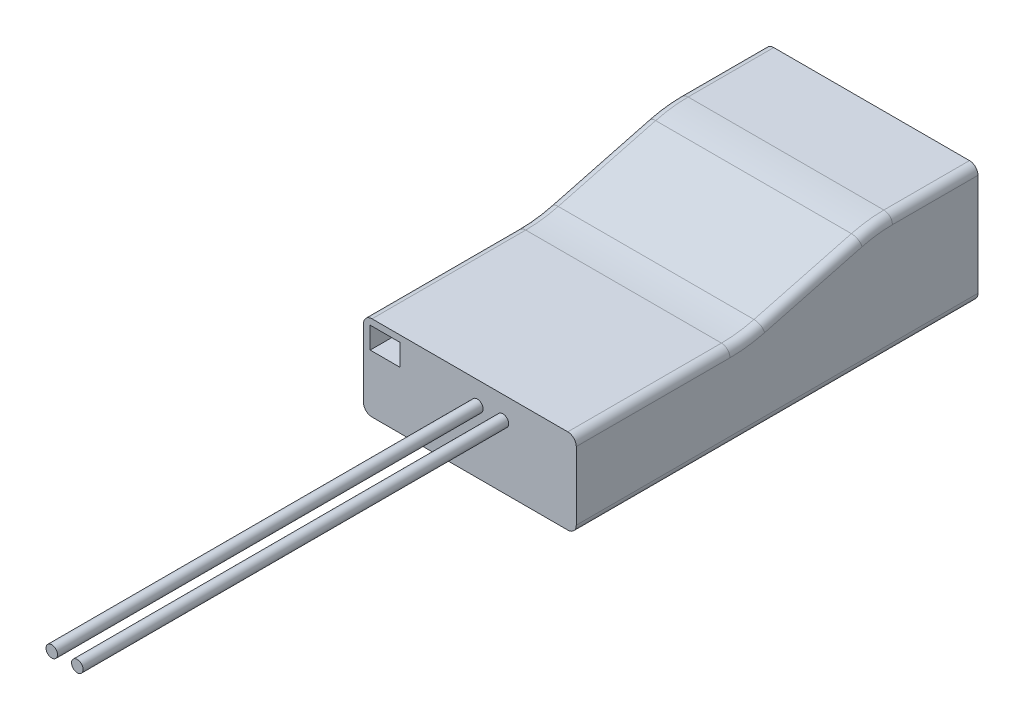
SolidWorks part; units mm, degrees
ref_plane "前基準面" through (0, 0, 0) normal (0, 0, 1) x (1, 0, 0)
ref_plane "上基準面" through (0, 0, 0) normal (0, 1, 0) x (1, 0, 0)
ref_plane "右基準面" through (0, 0, 0) normal (1, 0, 0) x (0, 0, -1)
sketch "草圖1" plane through (0, 0, 0) normal (0, 1, 0) x (1, 0, 0)
  line L1 (-12.5, 23.6) -> (12.5, 23.6)
  line L2 (-12.5, 23.6) -> (-12.5, -23.6)
  line L3 (-12.5, -23.6) -> (12.5, -23.6)
  line L4 (12.5, 23.6) -> (12.5, -23.6)
  line L5 (-12.5, 23.6) -> (12.5, -23.6) construction
  line L6 (-12.5, -23.6) -> (12.5, 23.6) construction
  point P0 (0, 0)
  dimension "D1" = 47.2
  dimension "D2" = 25
extrude "填料-伸長1" add sketch "草圖1" along normal blind 14
sketch "草圖2" plane through (12.5, 0, 0) normal (1, 0, 0) x (0, 0, -1)
  line L0 (-23.6, 10) -> (-3.6, 10)
  line L1 (-23.6, 14) -> (-23.6, 0) construction
  line L2 (-3.6, 10) -> (11.6, 14)
  line L3 (-23.6, 14) -> (23.6, 14) construction
  line L4 (11.6, 14) -> (-23.6, 14)
  line L5 (-23.6, 14) -> (-23.6, 10)
  line L6 (-23.6, 0) -> (23.6, 0) construction
  dimension "D1" = 20
  dimension "D2" = 10
  dimension "D3" = 12
extrude "除料-伸長1" cut sketch "草圖2" against normal through all
fillet "圓角1" radius 15 2 edges at (0, 14, -11.6) (0, 10, 3.6)
sketch "草圖3" plane through (0, 0, -23.6) normal (0, 0, -1) x (-1, 0, 0)
  line L0 (-12, 13.5) -> (-12, 0.5)
  line L1 (-12, 0.5) -> (12, 0.5)
  line L2 (12, 0.5) -> (12, 13.5)
  line L3 (12, 13.5) -> (-12, 13.5)
  line L4 (-12.5, 0) -> (12.5, 0)
  line L5 (12.5, 0) -> (12.5, 14)
  line L6 (12.5, 14) -> (-12.5, 14)
  line L7 (-12.5, 14) -> (-12.5, 0)
  line L8 (-12.5, 0) -> (12.5, 0) construction
  line L9 (12.5, 0) -> (12.5, 14) construction
  line L10 (12.5, 14) -> (-12.5, 14) construction
  line L11 (-12.5, 14) -> (-12.5, 0) construction
  circle A0 centre (-10.9486, 12.6433) radius 0.5
  circle A1 centre (-7.9486, 12.6433) radius 0.5
  circle A2 centre (-4.9486, 12.6433) radius 0.5
  circle A3 centre (-1.9486, 12.6433) radius 0.5
  circle A4 centre (1.0514, 12.6433) radius 0.5
  circle A5 centre (4.0514, 12.6433) radius 0.5
  circle A6 centre (7.0514, 12.6433) radius 0.5
  circle A7 centre (10.0514, 12.6433) radius 0.5
  circle A8 centre (-7.9486, 9.8433) radius 0.5
  circle A9 centre (-4.9486, 9.8433) radius 0.5
  circle A10 centre (-1.9486, 9.8433) radius 0.5
  circle A11 centre (1.0514, 9.8433) radius 0.5
  circle A12 centre (4.0514, 9.8433) radius 0.5
  circle A13 centre (7.0514, 9.8433) radius 0.5
  circle A14 centre (10.0514, 9.8433) radius 0.5
  circle A15 centre (-7.9486, 7.0433) radius 0.5
  circle A16 centre (-4.9486, 7.0433) radius 0.5
  circle A17 centre (-1.9486, 7.0433) radius 0.5
  circle A18 centre (1.0514, 7.0433) radius 0.5
  circle A19 centre (4.0514, 7.0433) radius 0.5
  circle A20 centre (7.0514, 7.0433) radius 0.5
  circle A21 centre (10.0514, 7.0433) radius 0.5
  circle A22 centre (-7.9486, 4.2433) radius 0.5
  circle A23 centre (-4.9486, 4.2433) radius 0.5
  circle A24 centre (-1.9486, 4.2433) radius 0.5
  circle A25 centre (1.0514, 4.2433) radius 0.5
  circle A26 centre (4.0514, 4.2433) radius 0.5
  circle A27 centre (7.0514, 4.2433) radius 0.5
  circle A28 centre (10.0514, 4.2433) radius 0.5
  circle A29 centre (-7.9486, 1.4433) radius 0.5
  circle A30 centre (-4.9486, 1.4433) radius 0.5
  circle A31 centre (-1.9486, 1.4433) radius 0.5
  circle A32 centre (1.0514, 1.4433) radius 0.5
  circle A33 centre (4.0514, 1.4433) radius 0.5
  circle A34 centre (7.0514, 1.4433) radius 0.5
  circle A35 centre (10.0514, 1.4433) radius 0.5
  circle A43 centre (-10.9486, 9.8433) radius 0.5
  circle A44 centre (-10.9486, 7.0433) radius 0.5
  circle A45 centre (-10.9486, 4.2433) radius 0.5
  circle A46 centre (-10.9486, 1.4433) radius 0.5
  circle A48 centre (-7.9486, -1.3567) radius 0.5 [skipped]
  circle A49 centre (-4.9486, -1.3567) radius 0.5 [skipped]
  circle A50 centre (-1.9486, -1.3567) radius 0.5 [skipped]
  circle A51 centre (1.0514, -1.3567) radius 0.5 [skipped]
  circle A52 centre (4.0514, -1.3567) radius 0.5 [skipped]
  circle A53 centre (7.0514, -1.3567) radius 0.5 [skipped]
  circle A54 centre (10.0514, -1.3567) radius 0.5 [skipped]
  circle A55 centre (-10.9486, -1.3567) radius 0.5 [skipped]
  dimension "D1" = 1
  dimension "D4" = 0
  dimension "D5" = 0.5
  dimension "D2" = 8
  dimension "D3" = 6
extrude "除料-伸長2" cut sketch "草圖3" against normal blind 5
sketch "草圖4" plane through (0, 0, 23.6) normal (0, 0, 1) x (1, 0, 0)
  line L1 (-11.7119, 9.2465) -> (-8.2255, 9.2465)
  line L2 (-11.7119, 9.2465) -> (-11.7119, 6.7109)
  line L3 (-11.7119, 6.7109) -> (-8.2255, 6.7109)
  line L4 (-8.2255, 9.2465) -> (-8.2255, 6.7109)
extrude "除料-伸長3" cut sketch "草圖4" against normal blind 5
sketch "草圖5" plane through (0, 0, 23.6) normal (0, 0, 1) x (1, 0, 0)
  circle A0 centre (0.8754, 7.3448) radius 0.6792
  circle A1 centre (3.8754, 7.3448) radius 0.6792
  dimension "D1" = 3
extrude "填料-伸長2" add sketch "草圖5" along normal blind 50
fillet "圓角2" radius 1 12 edges at (12.5, 14, -18.5703) (12.5, 13.876, -11.616) (12.5, 12, -4) (12.5, 10.124, 3.616) (-12.5, 10, 14.5703) (-12.5, 10.124, 3.616) (-12.5, 12, -4) (-12.5, 13.876, -11.616) (12.5, 0, 0) (12.5, 10, 14.5703) (-12.5, 0, 0) (-12.5, 14, -18.5703)
